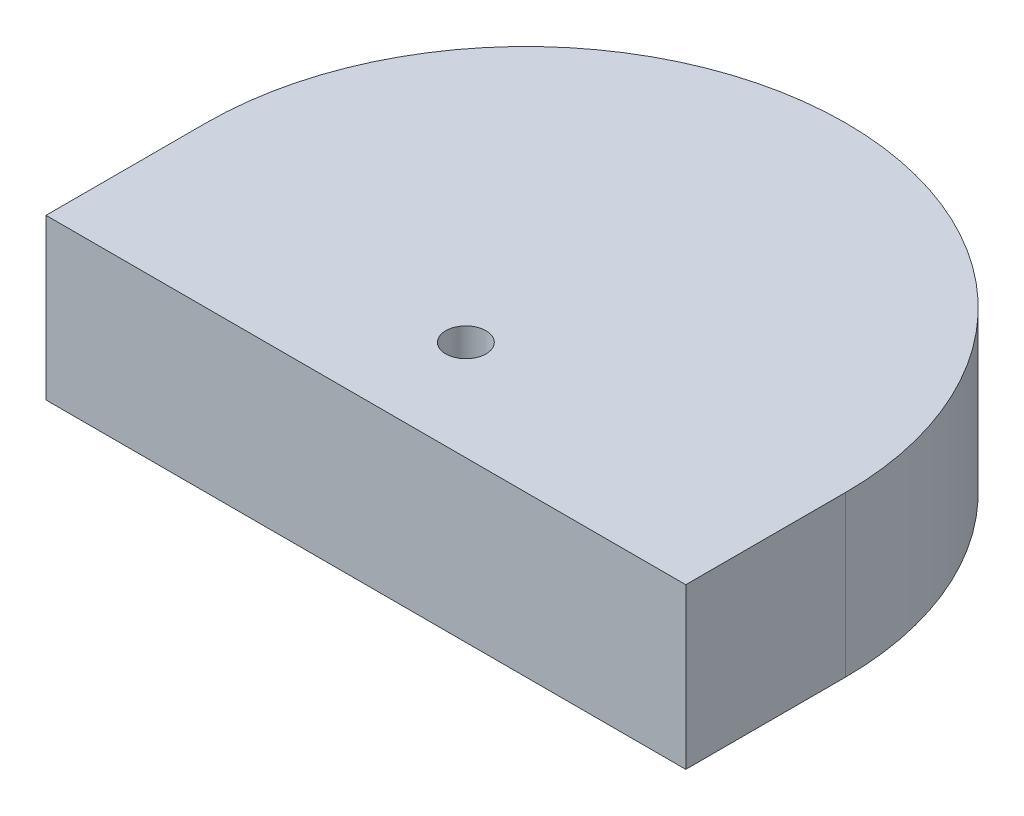
SolidWorks part; units mm, degrees
material "Oak"
ref_plane "Front Plane" through (0, 0, 0) normal (0, 0, 1) x (1, 0, 0)
ref_plane "Top Plane" through (0, 0, 0) normal (0, 1, 0) x (1, 0, 0)
ref_plane "Right Plane" through (0, 0, 0) normal (1, 0, 0) x (0, 0, -1)
sketch "Sketch1" plane through (0, 0, 0) normal (0, 1, 0) x (1, 0, 0)
  line L0 (-40, 0) -> (40, 0)
  arc A0 (40, 0) -> (-40, 0) centre (0, 0) ccw
  point P3 (0, 0)
  dimension "D1" = 80
extrude "Boss-Extrude1" add sketch "Sketch1" along normal blind 20
sketch "Sketch3" plane through (0, 20, 0) normal (0, 1, 0) x (1, 0, 0)
  line L1 (-40, -15) -> (40, -15)
  line L2 (-40, -15) -> (-40, 0)
  line L3 (-40, 0) -> (40, 0)
  line L4 (40, -15) -> (40, 0)
  arc A0 (40, 0) -> (-40, 0) centre (0, 0) ccw construction
  dimension "D1" = 15
extrude "Boss-Extrude3" add sketch "Sketch3" against normal blind 20
sketch "Sketch4" plane through (0, 0, 0) normal (0, -1, 0) x (-1, 0, 0)
  line L0 (-40, 0) -> (40, -15) construction
  circle A0 centre (0, -7.5) radius 1.75
  point P4 (0, -7.5)
extrude "Cut-Extrude1" cut sketch "Sketch4" against normal blind 20
sketch "Sketch6" plane through (0, 0, 0) normal (0, -1, 0) x (-1, 0, 0)
  line L0 (40, 0) -> (40, -15) construction
  line L1 (-40, -15) -> (40, -15)
  line L2 (-40, -15) -> (-40, -20)
  line L3 (-40, -20) -> (40, -20)
  line L4 (40, -15) -> (40, -20)
  dimension "D1" = 5
extrude "Boss-Extrude4" add sketch "Sketch6" against normal blind 20
sketch "Sketch7" plane through (0, 20, 0) normal (0, 1, 0) x (1, 0, 0)
  circle A0 centre (0, -7.5) radius 2.5182
extrude "Cut-Extrude3" cut sketch "Sketch7" against normal blind 20
